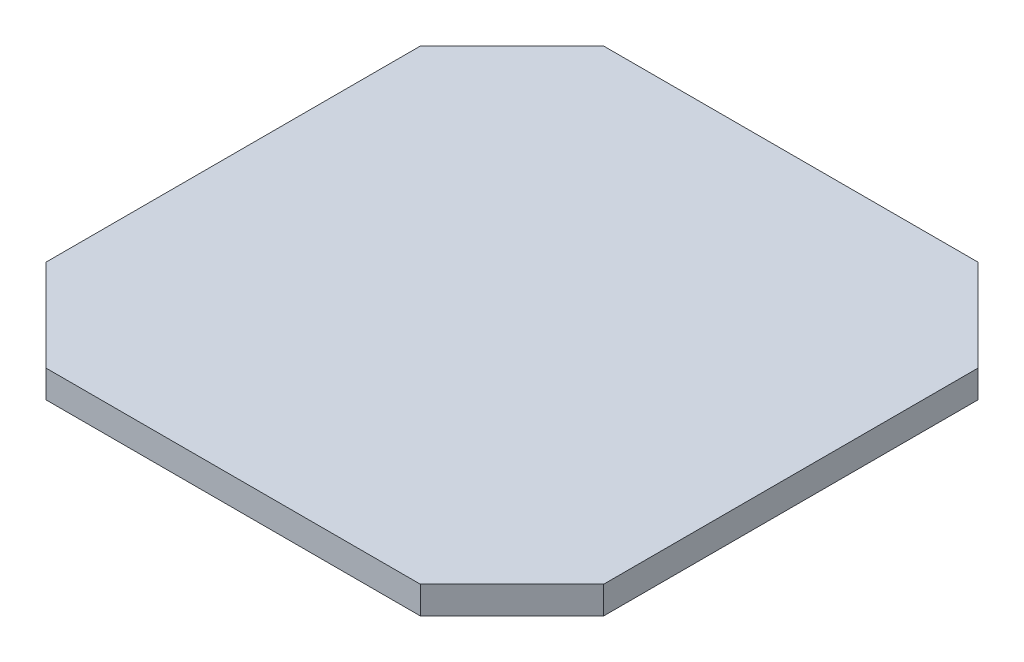
SolidWorks part; units mm, degrees
material "VITON"
ref_plane "Front Plane" through (0, 0, 0) normal (0, 0, 1) x (1, 0, 0)
ref_plane "Top Plane" through (0, 0, 0) normal (0, 1, 0) x (1, 0, 0)
ref_plane "Right Plane" through (0, 0, 0) normal (1, 0, 0) x (0, 0, -1)
sketch "Sketch2" plane through (0, 0, 0) normal (0, 1, 0) x (1, 0, 0)
  line L1 (0, 0) -> (6.08, 0)
  line L2 (0, 0) -> (0, 6.08)
  line L3 (0, 6.08) -> (6.08, 6.08)
  line L4 (6.08, 0) -> (6.08, 6.08)
  dimension "D1" = 6.08
  dimension "D2" = 6.08
extrude "Boss-Extrude1" add sketch "Sketch2" along normal blind 0.3
chamfer "Chamfer1" distance 1 angle 45 4 edges at (6.08, 0.15, -6.08) (0, 0.15, -6.08) (0, 0.15, 0) (6.08, 0.15, 0)
